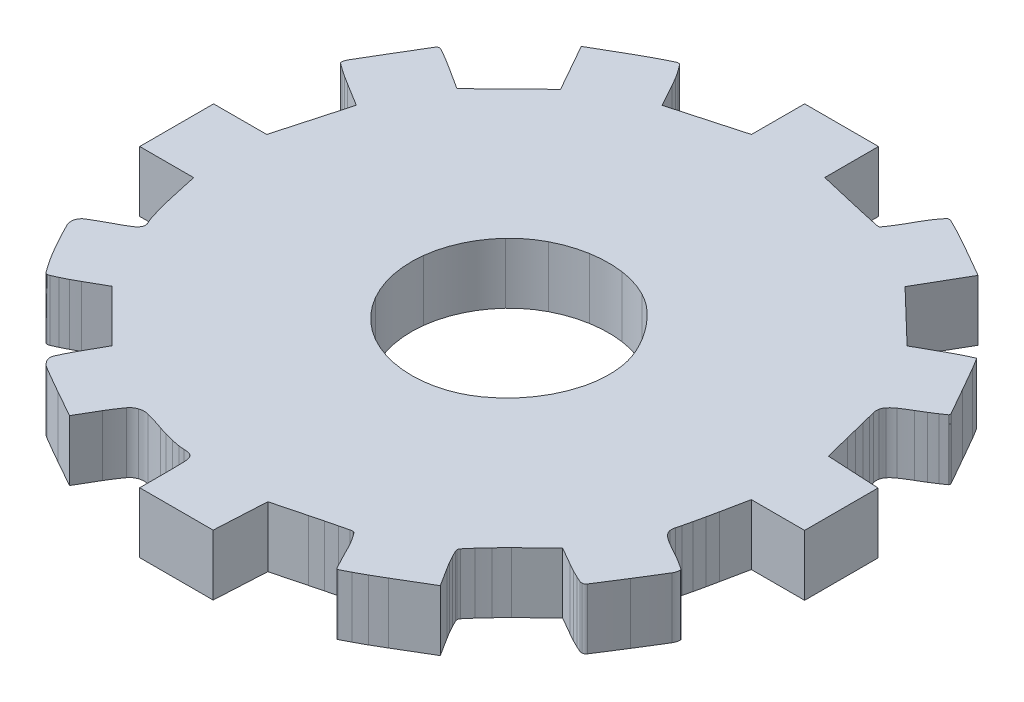
SolidWorks part; units mm, degrees
ref_plane "Front Plane" through (0, 0, 0) normal (0, 0, 1) x (1, 0, 0)
ref_plane "Top Plane" through (0, 0, 0) normal (0, 1, 0) x (1, 0, 0)
ref_plane "Right Plane" through (0, 0, 0) normal (1, 0, 0) x (0, 0, -1)
sketch "Sketch1" plane through (0, 0, 0) normal (0, 1, 0) x (1, 0, 0)
  line L235 (14951.9348, 3224.8737) -> (14951.9343, 3224.4355)
  line L236 (14951.9343, 3224.4355) -> (14951.357, 3224.2753)
  line L237 (14951.357, 3224.2753) -> (14950.7798, 3224.115)
  line L238 (14950.7798, 3224.115) -> (14950.5765, 3224.4837)
  line L239 (14949.7617, 3224.5725) -> (14949.2712, 3224.2904)
  line L240 (14949.2712, 3224.2904) -> (14949.4927, 3223.8978)
  line L241 (14949.4927, 3223.8978) -> (14949.7143, 3223.5052)
  line L242 (14949.7143, 3223.5052) -> (14949.2818, 3223.0828)
  line L243 (14949.2818, 3223.0828) -> (14948.8492, 3222.6604)
  line L244 (14948.8492, 3222.6604) -> (14948.5063, 3222.8797)
  line L245 (14947.8859, 3221.8205) -> (14948.256, 3221.5928)
  line L246 (14948.256, 3221.5928) -> (14948.0954, 3221.0144)
  line L247 (14948.0954, 3221.0144) -> (14947.9348, 3220.4361)
  line L248 (14947.9348, 3220.4361) -> (14947.4967, 3220.4355)
  line L249 (14947.4967, 3220.4355) -> (14947.0585, 3220.435)
  line L250 (14947.0585, 3220.435) -> (14947.0585, 3219.8254)
  line L251 (14947.0585, 3219.8254) -> (14947.0585, 3219.2158)
  line L252 (14947.0585, 3219.2158) -> (14947.5036, 3219.2158)
  line L253 (14947.5036, 3219.2158) -> (14947.9487, 3219.2158)
  line L254 (14947.9487, 3219.2158) -> (14948.0457, 3218.7777)
  line L255 (14948.5079, 3216.8079) -> (14948.8298, 3216.9907)
  line L256 (14948.8298, 3216.9907) -> (14949.2544, 3216.566)
  line L257 (14949.2544, 3216.566) -> (14949.6791, 3216.1414)
  line L258 (14949.6791, 3216.1414) -> (14949.4773, 3215.78)
  line L259 (14949.8921, 3215.0341) -> (14950.3254, 3214.7906)
  line L260 (14950.3254, 3214.7906) -> (14950.528, 3215.1363)
  line L261 (14951.9353, 3214.7962) -> (14951.9353, 3214.339)
  line L262 (14951.9353, 3214.339) -> (14952.5411, 3214.339)
  line L263 (14952.5411, 3214.339) -> (14953.1469, 3214.339)
  line L264 (14953.1469, 3214.339) -> (14953.1698, 3214.7675)
  line L265 (14953.1698, 3214.7675) -> (14953.1926, 3215.196)
  line L266 (14953.1926, 3215.196) -> (14953.726, 3215.3346)
  line L267 (14955.279, 3215.1009) -> (14955.815, 3215.4193)
  line L268 (14955.815, 3215.4193) -> (14955.6278, 3215.7158)
  line L269 (14955.8624, 3216.5514) -> (14956.2842, 3216.9679)
  line L270 (14956.2842, 3216.9679) -> (14956.5823, 3216.7965)
  line L271 (14957.0624, 3218.7777) -> (14957.1518, 3219.2158)
  line L272 (14957.1518, 3219.2158) -> (14957.5916, 3219.2158)
  line L273 (14957.5916, 3219.2158) -> (14958.0313, 3219.2158)
  line L274 (14958.0313, 3219.2158) -> (14958.0313, 3219.8216)
  line L275 (14958.0313, 3219.8216) -> (14958.0313, 3220.4274)
  line L276 (14958.0313, 3220.4274) -> (14957.5986, 3220.4503)
  line L277 (14957.5986, 3220.4503) -> (14957.1659, 3220.4731)
  line L278 (14957.1659, 3220.4731) -> (14957.0614, 3220.8922)
  line L279 (14957.0614, 3220.8922) -> (14957.0183, 3221.0644)
  line L280 (14957.0183, 3221.0644) -> (14956.9755, 3221.2353)
  line L281 (14956.9755, 3221.2353) -> (14956.9382, 3221.3836)
  line L282 (14957.5663, 3222.1009) -> (14957.3232, 3222.5288)
  line L283 (14956.6107, 3222.9044) -> (14956.2405, 3222.6977)
  line L284 (14956.2405, 3222.6977) -> (14955.8084, 3223.1129)
  line L285 (14955.8084, 3223.1129) -> (14955.3762, 3223.5281)
  line L286 (14955.3762, 3223.5281) -> (14955.5966, 3223.9098)
  line L287 (14955.5966, 3223.9098) -> (14955.8169, 3224.2914)
  line L288 (14955.8169, 3224.2914) -> (14955.3273, 3224.573)
  line L289 (14953.707, 3224.2961) -> (14953.1545, 3224.4253)
  line L290 (14953.1545, 3224.4253) -> (14953.1545, 3224.8686)
  line L291 (14953.1545, 3224.8686) -> (14953.1545, 3225.3118)
  line L292 (14953.1545, 3225.3118) -> (14952.5449, 3225.3118)
  line L293 (14952.5449, 3225.3118) -> (14951.9353, 3225.3118)
  line L294 (14951.9353, 3225.3118) -> (14951.9348, 3224.8737)
  arc A2929 (14950.5765, 3224.4837) -> (14950.4942, 3224.6251) centre (14947.4991, 3222.7871) ccw
  arc A2930 (14950.4942, 3224.6251) -> (14950.4152, 3224.7444) centre (14948.731, 3223.543) ccw
  arc A2931 (14950.4152, 3224.7444) -> (14950.3453, 3224.8374) centre (14948.5212, 3223.3934) ccw
  arc A2932 (14950.3453, 3224.8374) -> (14950.3127, 3224.8535) centre (14950.3119, 3224.811) ccw
  arc A2933 (14950.3127, 3224.8535) -> (14950.2721, 3224.8445) centre (14950.3111, 3224.7649) ccw
  arc A2934 (14950.2721, 3224.8445) -> (14950.1259, 3224.7714) centre (14954.6596, 3215.8815) ccw
  arc A2935 (14950.1259, 3224.7714) -> (14949.954, 3224.6805) centre (14953.0842, 3218.9706) ccw
  arc A2936 (14949.954, 3224.6805) -> (14949.7617, 3224.5725) centre (14955.1297, 3215.2392) ccw
  arc A2937 (14948.5063, 3222.8797) -> (14948.372, 3222.9639) centre (14944.0269, 3215.8787) ccw
  arc A2938 (14948.372, 3222.9639) -> (14948.2521, 3223.0351) centre (14945.7701, 3218.7211) ccw
  arc A2939 (14948.2521, 3223.0351) -> (14948.1499, 3223.093) centre (14944.2564, 3216.0903) ccw
  arc A2940 (14948.1499, 3223.093) -> (14948.1225, 3223.1006) centre (14948.1204, 3223.04) ccw
  arc A2941 (14948.1225, 3223.1006) -> (14948.0794, 3223.0772) centre (14948.1208, 3223.0523) ccw
  arc A2942 (14948.0794, 3223.0772) -> (14947.8041, 3222.6182) centre (15040.4187, 3167.3799) ccw
  arc A2943 (14947.8041, 3222.6182) -> (14947.5393, 3222.1699) centre (15001.9107, 3190.3472) ccw
  arc A2944 (14947.5393, 3222.1699) -> (14947.5157, 3222.0832) centre (14947.6874, 3222.0832) ccw
  arc A2945 (14947.5157, 3222.0832) -> (14947.526, 3222.0629) centre (14947.541, 3222.0832) ccw
  arc A2946 (14947.526, 3222.0629) -> (14947.6245, 3221.9917) centre (14951.4729, 3227.4142) ccw
  arc A2947 (14947.6245, 3221.9917) -> (14947.744, 3221.9104) centre (14949.7163, 3224.9391) ccw
  arc A2948 (14947.744, 3221.9104) -> (14947.8859, 3221.8205) centre (14951.3216, 3227.4043) ccw
  arc A2949 (14948.0457, 3218.7777) -> (14948.088, 3218.6003) centre (14953.7213, 3220.0349) ccw
  arc A2950 (14948.088, 3218.6003) -> (14948.1345, 3218.4297) centre (14953.0744, 3219.8702) ccw
  arc A2951 (14948.1345, 3218.4297) -> (14948.1792, 3218.2854) centre (14952.5971, 3219.731) ccw
  arc A2952 (14948.1792, 3218.2854) -> (14948.2117, 3218.2085) centre (14948.6525, 3218.4402) ccw
  arc A2953 (14948.2305, 3218.1356) -> (14948.2117, 3218.2085) centre (14948.0668, 3218.1323) ccw
  arc A2954 (14948.21, 3218.0733) -> (14948.2305, 3218.1356) centre (14948.1319, 3218.1336) ccw
  arc A2955 (14948.1399, 3218.0099) -> (14948.21, 3218.0733) centre (14947.9986, 3218.2365) ccw
  arc A2956 (14947.9934, 3217.9257) -> (14948.1399, 3218.0099) centre (14946.8916, 3220.0111) ccw
  arc A2957 (14947.9934, 3217.9257) -> (14947.6463, 3217.7315) centre (14951.8782, 3210.573) ccw
  arc A2958 (14947.6463, 3217.7315) -> (14947.5669, 3217.6275) centre (14947.735, 3217.5815) ccw
  arc A2959 (14947.5669, 3217.6275) -> (14947.5802, 3217.4951) centre (14947.7457, 3217.5786) ccw
  arc A2960 (14947.5802, 3217.4951) -> (14947.7753, 3217.1281) centre (14956.2631, 3221.8748) ccw
  arc A2961 (14947.7753, 3217.1281) -> (14947.8878, 3216.9353) centre (14953.0962, 3220.1037) ccw
  arc A2962 (14947.8878, 3216.9353) -> (14947.993, 3216.7728) centre (14950.8426, 3218.7328) ccw
  arc A2963 (14947.993, 3216.7728) -> (14948.0854, 3216.6431) centre (14951.876, 3219.4436) ccw
  arc A2964 (14948.0854, 3216.6431) -> (14948.1213, 3216.625) centre (14948.1213, 3216.6696) ccw
  arc A2965 (14948.1213, 3216.625) -> (14948.1615, 3216.6334) centre (14948.1213, 3216.7259) ccw
  arc A2966 (14948.1615, 3216.6334) -> (14948.2615, 3216.6787) centre (14946.8059, 3219.7564) ccw
  arc A2967 (14948.2615, 3216.6787) -> (14948.3799, 3216.7378) centre (14946.9413, 3219.4702) ccw
  arc A2968 (14948.3799, 3216.7378) -> (14948.5079, 3216.8079) centre (14946.2517, 3220.7799) ccw
  arc A2969 (14949.4773, 3215.78) -> (14949.3454, 3215.5147) centre (14952.179, 3214.2716) ccw
  arc A2970 (14949.3454, 3215.5147) -> (14949.3512, 3215.3934) centre (14949.4706, 3215.4598) ccw
  arc A2971 (14949.3512, 3215.3934) -> (14949.4542, 3215.2873) centre (14949.5994, 3215.5315) ccw
  arc A2972 (14949.4542, 3215.2873) -> (14949.8921, 3215.0341) centre (14959.9608, 3232.9506) ccw
  arc A2973 (14950.6836, 3215.3734) -> (14950.528, 3215.1363) centre (14952.9466, 3213.7189) ccw
  arc A2974 (14950.7996, 3215.4571) -> (14950.6836, 3215.3734) centre (14950.8702, 3215.237) ccw
  arc A2975 (14950.9486, 3215.4608) -> (14950.7996, 3215.4571) centre (14950.8804, 3215.2053) ccw
  arc A2976 (14951.2495, 3215.3677) -> (14950.9486, 3215.4608) centre (14949.9117, 3211.5759) ccw
  arc A2977 (14951.2495, 3215.3677) -> (14951.3868, 3215.324) centre (14952.0311, 3217.583) ccw
  arc A2978 (14951.3868, 3215.324) -> (14951.5315, 3215.287) centre (14952.1288, 3217.9255) ccw
  arc A2979 (14951.5315, 3215.287) -> (14951.663, 3215.2611) centre (14952.0611, 3217.6264) ccw
  arc A2980 (14951.663, 3215.2611) -> (14951.7544, 3215.2534) centre (14951.7544, 3215.8041) ccw
  arc A2981 (14951.8564, 3215.2363) -> (14951.7544, 3215.2534) centre (14951.7544, 3214.941) ccw
  arc A2982 (14951.9088, 3215.1862) -> (14951.8564, 3215.2363) centre (14951.8281, 3215.1543) ccw
  arc A2983 (14951.9311, 3215.0781) -> (14951.9088, 3215.1862) centre (14951.6109, 3215.0684) ccw
  arc A2984 (14951.9353, 3214.7962) -> (14951.9311, 3215.0781) centre (14942.6163, 3214.7962) ccw
  arc A2985 (14953.9344, 3215.388) -> (14953.726, 3215.3346) centre (14961.9605, 3183.6501) ccw
  arc A2986 (14954.1191, 3215.4338) -> (14953.9344, 3215.388) centre (14958.8499, 3195.9506) ccw
  arc A2987 (14954.2758, 3215.4715) -> (14954.1191, 3215.4338) centre (14961.8698, 3183.5134) ccw
  arc A2988 (14954.315, 3215.4776) -> (14954.2758, 3215.4715) centre (14954.3353, 3215.2213) ccw
  arc A2989 (14954.3443, 3215.4647) -> (14954.315, 3215.4776) centre (14954.3177, 3215.4439) ccw
  arc A2990 (14954.4023, 3215.3856) -> (14954.3443, 3215.4647) centre (14953.107, 3214.4979) ccw
  arc A2991 (14954.4673, 3215.2819) -> (14954.4023, 3215.3856) centre (14953.1472, 3214.5255) ccw
  arc A2992 (14954.534, 3215.1582) -> (14954.4673, 3215.2819) centre (14952.1766, 3213.9694) ccw
  arc A2993 (14954.534, 3215.1582) -> (14954.5982, 3215.0322) centre (14968.5438, 3222.2232) ccw
  arc A2994 (14954.5982, 3215.0322) -> (14954.656, 3214.9218) centre (14963.0236, 3219.3767) ccw
  arc A2995 (14954.656, 3214.9218) -> (14954.706, 3214.8287) centre (14968.9809, 3222.5484) ccw
  arc A2996 (14954.706, 3214.8287) -> (14954.7202, 3214.8084) centre (14954.8016, 3214.8803) ccw
  arc A2997 (14954.7202, 3214.8084) -> (14954.7405, 3214.8045) centre (14954.7329, 3214.8196) ccw
  arc A2998 (14954.7405, 3214.8045) -> (14954.8938, 3214.8836) centre (14947.8369, 3228.3673) ccw
  arc A2999 (14954.8938, 3214.8836) -> (14955.0719, 3214.9807) centre (14952.0837, 3220.2528) ccw
  arc A3000 (14955.0719, 3214.9807) -> (14955.279, 3215.1009) centre (14949.29, 3225.182) ccw
  arc A3001 (14955.556, 3215.8339) -> (14955.6278, 3215.7158) centre (14959.01, 3217.8509) ccw
  arc A3002 (14955.4955, 3215.9433) -> (14955.556, 3215.8339) centre (14957.8758, 3217.1886) ccw
  arc A3003 (14955.4491, 3216.0359) -> (14955.4955, 3215.9433) centre (14958.1031, 3217.3075) ccw
  arc A3004 (14955.4405, 3216.0737) -> (14955.4491, 3216.0359) centre (14955.5278, 3216.0737) ccw
  arc A3005 (14955.4545, 3216.1119) -> (14955.4405, 3216.0737) centre (14955.4999, 3216.0737) ccw
  arc A3006 (14955.5645, 3216.2393) -> (14955.4545, 3216.1119) centre (14961.1837, 3211.2777) ccw
  arc A3007 (14955.7007, 3216.3874) -> (14955.5645, 3216.2393) centre (14959.2428, 3212.9915) ccw
  arc A3008 (14955.8624, 3216.5514) -> (14955.7007, 3216.3874) centre (14961.7586, 3210.5795) ccw
  arc A3009 (14956.5823, 3216.7965) -> (14956.7012, 3216.7308) centre (14958.5463, 3220.2112) ccw
  arc A3010 (14956.7012, 3216.7308) -> (14956.8118, 3216.6754) centre (14957.9718, 3219.1277) ccw
  arc A3011 (14956.8118, 3216.6754) -> (14956.9053, 3216.6331) centre (14958.0442, 3219.2806) ccw
  arc A3012 (14956.9053, 3216.6331) -> (14956.9448, 3216.625) centre (14956.9448, 3216.7248) ccw
  arc A3013 (14956.9448, 3216.625) -> (14957.0042, 3216.6574) centre (14956.9448, 3216.6957) ccw
  arc A3014 (14957.0042, 3216.6574) -> (14957.2804, 3217.0912) centre (14911.8993, 3245.6842) ccw
  arc A3015 (14957.2804, 3217.0912) -> (14957.5439, 3217.5163) centre (14928.2823, 3235.3619) ccw
  arc A3016 (14957.5439, 3217.5163) -> (14957.5741, 3217.6239) centre (14957.3674, 3217.6239) ccw
  arc A3017 (14957.5741, 3217.6239) -> (14957.5642, 3217.6426) centre (14957.5517, 3217.6239) ccw
  arc A3018 (14957.5642, 3217.6426) -> (14957.4723, 3217.7027) centre (14954.5695, 3213.1679) ccw
  arc A3019 (14957.4723, 3217.7027) -> (14957.3604, 3217.771) centre (14955.8263, 3215.1313) ccw
  arc A3020 (14957.3604, 3217.771) -> (14957.2275, 3217.8458) centre (14954.5674, 3212.9649) ccw
  arc A3021 (14957.0499, 3217.95) -> (14957.2275, 3217.8458) centre (14958.7905, 3220.7135) ccw
  arc A3022 (14956.959, 3218.0275) -> (14957.0499, 3217.95) centre (14957.2729, 3218.3039) ccw
  arc A3023 (14956.9225, 3218.1017) -> (14956.959, 3218.0275) centre (14957.0771, 3218.1315) ccw
  arc A3024 (14956.9269, 3218.1871) -> (14956.9225, 3218.1017) centre (14957.0979, 3218.1355) ccw
  arc A3025 (14956.9269, 3218.1871) -> (14956.9502, 3218.2728) centre (14955.408, 3218.6457) ccw
  arc A3026 (14956.9502, 3218.2728) -> (14956.9857, 3218.4235) centre (14944.2274, 3221.3496) ccw
  arc A3027 (14956.9857, 3218.4235) -> (14957.0248, 3218.5987) centre (14942.8463, 3221.6664) ccw
  arc A3028 (14957.0248, 3218.5987) -> (14957.0624, 3218.7777) centre (14941.793, 3221.8943) ccw
  arc A3029 (14956.9382, 3221.3836) -> (14956.9158, 3221.4716) centre (14931.2925, 3214.9195) ccw
  arc A3030 (14956.914, 3221.5617) -> (14956.9158, 3221.4716) centre (14957.1076, 3221.5206) ccw
  arc A3031 (14956.9527, 3221.6407) -> (14956.914, 3221.5617) centre (14957.0905, 3221.5242) ccw
  arc A3032 (14957.0457, 3221.7242) -> (14956.9527, 3221.6407) centre (14957.3001, 3221.347) ccw
  arc A3033 (14957.2245, 3221.8367) -> (14957.0457, 3221.7242) centre (14958.9083, 3218.9636) ccw
  arc A3034 (14957.2245, 3221.8367) -> (14957.3585, 3221.9174) centre (14953.8502, 3227.5945) ccw
  arc A3035 (14957.3585, 3221.9174) -> (14957.4714, 3221.9901) centre (14955.4461, 3225.0122) ccw
  arc A3036 (14957.4714, 3221.9901) -> (14957.5652, 3222.054) centre (14953.3895, 3228.0807) ccw
  arc A3037 (14957.5652, 3222.054) -> (14957.5741, 3222.0711) centre (14957.5534, 3222.0711) ccw
  arc A3038 (14957.5741, 3222.0711) -> (14957.5663, 3222.1009) centre (14957.5137, 3222.0711) ccw
  arc A3039 (14957.3232, 3222.5288) -> (14957.1037, 3222.9119) centre (14899.5992, 3189.7053) ccw
  arc A3040 (14957.1037, 3222.9119) -> (14956.9962, 3223.0875) centre (14953.6526, 3220.919) ccw
  arc A3041 (14956.9962, 3223.0875) -> (14956.981, 3223.0919) centre (14956.986, 3223.0809) ccw
  arc A3042 (14956.981, 3223.0919) -> (14956.8766, 3223.0434) centre (14959.8455, 3216.7929) ccw
  arc A3043 (14956.8766, 3223.0434) -> (14956.7537, 3222.982) centre (14958.3159, 3220.0134) ccw
  arc A3044 (14956.7537, 3222.982) -> (14956.6107, 3222.9044) centre (14959.8086, 3217.1767) ccw
  arc A3045 (14955.3273, 3224.573) -> (14955.1352, 3224.6809) centre (14949.9456, 3215.2159) ccw
  arc A3046 (14955.1352, 3224.6809) -> (14954.9633, 3224.7719) centre (14951.976, 3218.919) ccw
  arc A3047 (14954.9633, 3224.7719) -> (14954.8171, 3224.845) centre (14950.4743, 3215.9768) ccw
  arc A3048 (14954.8171, 3224.845) -> (14954.7756, 3224.8546) centre (14954.7756, 3224.7603) ccw
  arc A3049 (14954.7756, 3224.8546) -> (14954.7426, 3224.839) centre (14954.7756, 3224.8119) ccw
  arc A3050 (14954.7426, 3224.839) -> (14954.6767, 3224.7539) centre (14956.1392, 3223.69) ccw
  arc A3051 (14954.6767, 3224.7539) -> (14954.6024, 3224.6431) centre (14956.0812, 3223.7322) ccw
  arc A3052 (14954.6024, 3224.6431) -> (14954.5261, 3224.5117) centre (14957.0852, 3223.1138) ccw
  arc A3053 (14954.4515, 3224.3802) -> (14954.5261, 3224.5117) centre (14950.4905, 3226.7163) ccw
  arc A3054 (14954.3822, 3224.2693) -> (14954.4515, 3224.3802) centre (14952.2248, 3225.6935) ccw
  arc A3055 (14954.3212, 3224.1797) -> (14954.3822, 3224.2693) centre (14951.1743, 3226.3869) ccw
  arc A3056 (14954.2991, 3224.1678) -> (14954.3212, 3224.1797) centre (14954.2984, 3224.1956) ccw
  arc A3057 (14954.2699, 3224.1706) -> (14954.2991, 3224.1678) centre (14954.296, 3224.2937) ccw
  arc A3058 (14954.1088, 3224.2051) -> (14954.2699, 3224.1706) centre (14963.1969, 3266.1712) ccw
  arc A3059 (14953.9216, 3224.2466) -> (14954.1088, 3224.2051) centre (14958.2008, 3243.1006) ccw
  arc A3060 (14953.707, 3224.2961) -> (14953.9216, 3224.2466) centre (14961.3426, 3256.9431) ccw
  arc A3061 (14953.6032, 3221.0441) -> (14953.314, 3221.2498) centre (14952.7077, 3220.0915) ccw
  arc A3062 (14953.8678, 3220.7431) -> (14953.6032, 3221.0441) centre (14952.1586, 3219.5074) ccw
  arc A3063 (14954.0701, 3220.3982) -> (14953.8678, 3220.7431) centre (14952.1652, 3219.5122) ccw
  arc A3064 (14954.1732, 3220.0614) -> (14954.0701, 3220.3982) centre (14952.9125, 3219.8598) ccw
  arc A3065 (14954.1486, 3219.4699) -> (14954.1732, 3220.0614) centre (14952.7038, 3219.8264) ccw
  arc A3066 (14953.8972, 3218.9061) -> (14954.1486, 3219.4699) centre (14952.4515, 3219.8887) ccw
  arc A3067 (14953.4658, 3218.4652) -> (14953.8972, 3218.9061) centre (14952.4534, 3219.8873) ccw
  arc A3068 (14952.9255, 3218.2255) -> (14953.4658, 3218.4652) centre (14952.6072, 3219.6714) ccw
  arc A3069 (14951.9137, 3218.3267) -> (14952.9255, 3218.2255) centre (14952.5742, 3219.8211) ccw
  arc A3070 (14951.1601, 3219.0068) -> (14951.9137, 3218.3267) centre (14952.57, 3219.8116) ccw
  arc A3071 (14950.9584, 3220.0006) -> (14951.1601, 3219.0068) centre (14952.5662, 3219.8095) ccw
  arc A3072 (14951.3869, 3220.9209) -> (14950.9584, 3220.0006) centre (14952.573, 3219.8087) ccw
  arc A3073 (14951.7952, 3221.2291) -> (14951.3869, 3220.9209) centre (14952.4848, 3219.8914) ccw
  arc A3074 (14952.2985, 3221.3973) -> (14951.7952, 3221.2291) centre (14952.5905, 3219.6863) ccw
  arc A3075 (14952.8284, 3221.4055) -> (14952.2985, 3221.3973) centre (14952.5898, 3219.6905) ccw
  arc A3076 (14953.314, 3221.2498) -> (14952.8284, 3221.4055) centre (14952.6231, 3219.93) ccw
extrude "Boss-Extrude1" add sketch "Sketch1" along normal blind 1
scale "Scale1" scale about centroid uniform scaling yes scale factor 18
